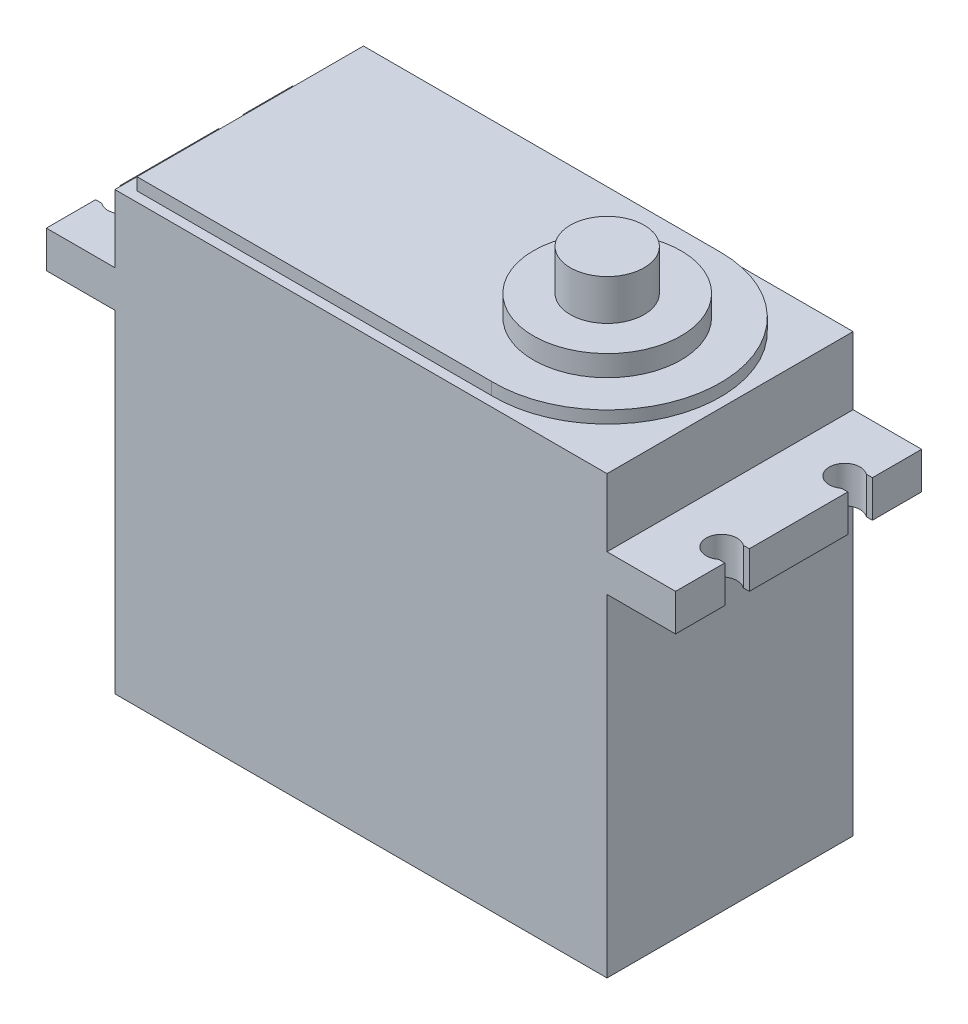
SolidWorks part; units mm, degrees
ref_plane "Plano frontal" through (0, 0, 0) normal (0, 0, 1) x (1, 0, 0)
ref_plane "Plano superior" through (0, 0, 0) normal (0, 1, 0) x (1, 0, 0)
ref_plane "Plano direito" through (0, 0, 0) normal (1, 0, 0) x (0, 0, -1)
sketch "Esboço1" plane through (0, 0, 0) normal (0, 0, 1) x (1, 0, 0)
  line L0 (20, -0.7679) -> (25.5689, -0.7679)
  line L1 (25.5689, -0.7679) -> (25.5689, -3.7679)
  line L2 (25.5689, -3.7679) -> (20, -3.7679)
  line L3 (20, -3.7679) -> (20, -30.7679)
  line L4 (20, -30.7679) -> (-20, -30.7679)
  line L5 (0, -30.7679) -> (0, 0) construction
  line L6 (20, -0.7679) -> (20, 4.7321)
  line L7 (20, 4.7321) -> (-20, 4.7321)
  line L8 (-20, -0.7679) -> (-20, 4.7321)
  line L9 (-20, -3.7679) -> (-20, -30.7679)
  line L10 (-25.5689, -3.7679) -> (-20, -3.7679)
  line L11 (-25.5689, -0.7679) -> (-25.5689, -3.7679)
  line L12 (-20, -0.7679) -> (-25.5689, -0.7679)
  point P11 (0, 4.7321)
  dimension "D1" = 40
  dimension "D2" = 27
  dimension "D3" = 3
  dimension "D4" = 5.5
extrude "Ressalto-extrusão1" add sketch "Esboço1" along normal mid plane 20
sketch "Esboço6" plane through (0, -0.7679, 0) normal (0, 1, 0) x (1, 0, 0)
  line L0 (0, 10) -> (0, -10) construction
  line L1 (20, 10) -> (-20, 10) construction
  line L2 (20, -10) -> (-20, -10) construction
  line L3 (24.315, 5) -> (24.315, -5) construction
  line L4 (20, -10) -> (20, 10) construction
  line L5 (25.5689, 4) -> (25.0714, 4)
  line L6 (25.5689, -10) -> (25.5689, 10) construction
  line L7 (25.0714, 6) -> (25.5689, 6)
  line L8 (24.315, 5) -> (25.5689, 5) construction
  line L9 (25.5689, 6) -> (25.5689, 4)
  line L10 (20, 0) -> (25.5689, 0) construction
  line L11 (25.5689, -6) -> (25.5689, -4)
  line L12 (25.0714, -6) -> (25.5689, -6)
  line L13 (25.5689, -4) -> (25.0714, -4)
  line L14 (-25.5689, -4) -> (-25.0714, -4)
  line L15 (-25.0714, -6) -> (-25.5689, -6)
  line L16 (-25.5689, -6) -> (-25.5689, -4)
  line L17 (-25.5689, 6) -> (-25.5689, 4)
  line L18 (-25.0714, 6) -> (-25.5689, 6)
  line L19 (-25.5689, 4) -> (-25.0714, 4)
  arc A0 (25.0714, 6) -> (25.0714, 4) centre (24.315, 5) ccw
  arc A1 (25.0714, -4) -> (25.0714, -6) centre (24.315, -5) ccw
  arc A2 (-25.0714, -4) -> (-25.0714, -6) centre (-24.315, -5) cw
  arc A3 (-25.0714, 6) -> (-25.0714, 4) centre (-24.315, 5) cw
  point P14 (24.315, 0)
  point P17 (20, 0)
  line M4 (25.5689, -10) -> (25.5689, 10)
  dimension "D1" = 48.63
  dimension "D2" = 10
  dimension "D3" = 2
extrude "Corte-extrusão1" cut sketch "Esboço6" against normal blind 10 contours L7 A0 L5 M4 | L13 A1 L12 M4 | A3 L18 L17 L19 | A2 L14 L16 L15
sketch "Esboço3" plane through (0, 4.7321, 0) normal (0, 1, 0) x (1, 0, 0)
  line L0 (20, -10) -> (-20, -10) construction
  line L1 (-19, 9.2025) -> (10.015, 9.2025)
  line L2 (-19, 9.2025) -> (-19, -9.2)
  line L3 (-19, -9.2) -> (9.8, -9.2)
  arc A0 (25.0714, -4) -> (25.0714, -6) centre (24.315, -5) ccw construction
  arc A1 (9.8, -9.2) -> (10.015, 9.2025) centre (10.015, 0) ccw
  point P0 (0, 0)
  dimension "D1" = 0.8
  dimension "D2" = 14.3
extrude "Ressalto-extrusão2" add sketch "Esboço3" along normal blind 1
sketch "Esboço4" plane through (0, 5.7321, 0) normal (0, 1, 0) x (1, 0, 0)
  circle A0 centre (10.015, 0) radius 3
extrude "Ressalto-extrusão3" add sketch "Esboço4" along normal blind 5
sketch "Esboço5" plane through (0, 5.7321, 0) normal (0, 1, 0) x (1, 0, 0)
  circle A0 centre (10.015, 0) radius 6
  arc A1 (25.0714, -4) -> (25.0714, -6) centre (24.315, -5) ccw construction
  point P3 (0, 0)
  dimension "D1" = 14.3
extrude "Ressalto-extrusão4" add sketch "Esboço5" along normal blind 1.7
